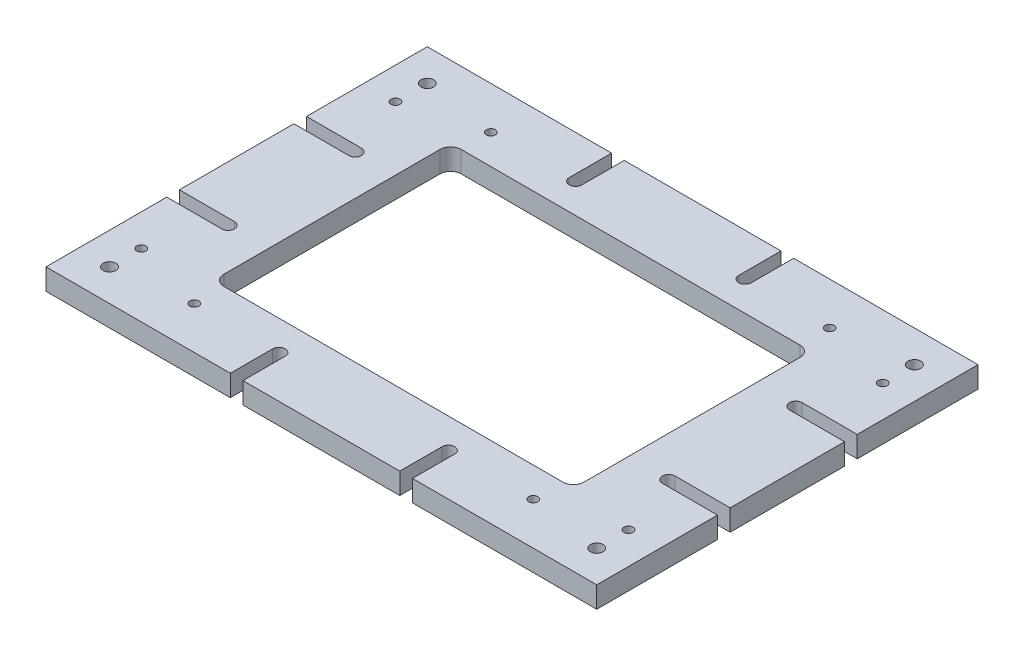
SolidWorks part; units mm, degrees
material "6061 Alloy"
ref_plane "Front Plane" through (0, 0, 0) normal (0, 0, 1) x (1, 0, 0)
ref_plane "Top Plane" through (0, 0, 0) normal (0, 1, 0) x (1, 0, 0)
ref_plane "Right Plane" through (0, 0, 0) normal (1, 0, 0) x (0, 0, -1)
sketch "Sketch1" plane through (0, 0, 0) normal (0, 1, 0) x (1, 0, 0)
  line L1 (-82.55, -57.15) -> (82.55, -57.15)
  line L2 (-82.55, -57.15) -> (-82.55, 57.15)
  line L3 (-82.55, 57.15) -> (82.55, 57.15)
  line L4 (82.55, -57.15) -> (82.55, 57.15)
  line L5 (-82.55, -57.15) -> (82.55, 57.15) construction
  line L6 (-82.55, 57.15) -> (82.55, -57.15) construction
  point P0 (0, 0)
  dimension "D1" = 165.1
  dimension "D2" = 114.3
extrude "Boss-Extrude1" add sketch "Sketch1" along normal blind 6.35
sketch "Sketch2" plane through (0, 6.35, 0) normal (0, 1, 0) x (1, 0, 0)
  line L0 (-49.5, -31.5) -> (-40.5, -31.5) construction
  line L1 (-49.5, -31.5) -> (-49.5, -22.5) construction
  line L2 (-82.55, 57.15) -> (-82.55, -57.15) construction
  line L3 (-82.55, -57.15) -> (82.55, -57.15) construction
  line L4 (-49.5, -31.5) -> (-49.5, 31.5) construction
  line L5 (-49.5, -31.5) -> (49.5, -31.5) construction
  line L6 (82.55, -57.15) -> (82.55, 57.15) construction
  line L9 (82.55, 57.15) -> (-82.55, 57.15) construction
  line L10 (0, 57.15) -> (0, -57.15) construction
  line L11 (-82.55, 0) -> (82.55, 0) construction
  circle A0 centre (-49.5, -31.5) radius 0.635
  circle A1 centre (-40.5, -31.5) radius 0.635
  circle A2 centre (-31.5, -31.5) radius 0.635
  circle A3 centre (-22.5, -31.5) radius 0.635
  circle A4 centre (-13.5, -31.5) radius 0.635
  circle A5 centre (-4.5, -31.5) radius 0.635
  circle A6 centre (4.5, -31.5) radius 0.635
  circle A7 centre (13.5, -31.5) radius 0.635
  circle A8 centre (22.5, -31.5) radius 0.635
  circle A9 centre (31.5, -31.5) radius 0.635
  circle A10 centre (40.5, -31.5) radius 0.635
  circle A11 centre (49.5, -31.5) radius 0.635
  circle A12 centre (-49.5, -22.5) radius 0.635
  circle A13 centre (-40.5, -22.5) radius 0.635
  circle A14 centre (-31.5, -22.5) radius 0.635
  circle A15 centre (-22.5, -22.5) radius 0.635
  circle A16 centre (-13.5, -22.5) radius 0.635
  circle A17 centre (-4.5, -22.5) radius 0.635
  circle A18 centre (4.5, -22.5) radius 0.635
  circle A19 centre (13.5, -22.5) radius 0.635
  circle A20 centre (22.5, -22.5) radius 0.635
  circle A21 centre (31.5, -22.5) radius 0.635
  circle A22 centre (40.5, -22.5) radius 0.635
  circle A23 centre (49.5, -22.5) radius 0.635
  circle A24 centre (-49.5, -13.5) radius 0.635
  circle A25 centre (-40.5, -13.5) radius 0.635
  circle A26 centre (-31.5, -13.5) radius 0.635
  circle A27 centre (-22.5, -13.5) radius 0.635
  circle A28 centre (-13.5, -13.5) radius 0.635
  circle A29 centre (-4.5, -13.5) radius 0.635
  circle A30 centre (4.5, -13.5) radius 0.635
  circle A31 centre (13.5, -13.5) radius 0.635
  circle A32 centre (22.5, -13.5) radius 0.635
  circle A33 centre (31.5, -13.5) radius 0.635
  circle A34 centre (40.5, -13.5) radius 0.635
  circle A35 centre (49.5, -13.5) radius 0.635
  circle A36 centre (-49.5, -4.5) radius 0.635
  circle A37 centre (-40.5, -4.5) radius 0.635
  circle A38 centre (-31.5, -4.5) radius 0.635
  circle A39 centre (-22.5, -4.5) radius 0.635
  circle A40 centre (-13.5, -4.5) radius 0.635
  circle A41 centre (-4.5, -4.5) radius 0.635
  circle A42 centre (4.5, -4.5) radius 0.635
  circle A43 centre (13.5, -4.5) radius 0.635
  circle A44 centre (22.5, -4.5) radius 0.635
  circle A45 centre (31.5, -4.5) radius 0.635
  circle A46 centre (40.5, -4.5) radius 0.635
  circle A47 centre (49.5, -4.5) radius 0.635
  circle A48 centre (-49.5, 4.5) radius 0.635
  circle A49 centre (-40.5, 4.5) radius 0.635
  circle A50 centre (-31.5, 4.5) radius 0.635
  circle A51 centre (-22.5, 4.5) radius 0.635
  circle A52 centre (-13.5, 4.5) radius 0.635
  circle A53 centre (-4.5, 4.5) radius 0.635
  circle A54 centre (4.5, 4.5) radius 0.635
  circle A55 centre (13.5, 4.5) radius 0.635
  circle A56 centre (22.5, 4.5) radius 0.635
  circle A57 centre (31.5, 4.5) radius 0.635
  circle A58 centre (40.5, 4.5) radius 0.635
  circle A59 centre (49.5, 4.5) radius 0.635
  circle A60 centre (-49.5, 13.5) radius 0.635
  circle A61 centre (-40.5, 13.5) radius 0.635
  circle A62 centre (-31.5, 13.5) radius 0.635
  circle A63 centre (-22.5, 13.5) radius 0.635
  circle A64 centre (-13.5, 13.5) radius 0.635
  circle A65 centre (-4.5, 13.5) radius 0.635
  circle A66 centre (4.5, 13.5) radius 0.635
  circle A67 centre (13.5, 13.5) radius 0.635
  circle A68 centre (22.5, 13.5) radius 0.635
  circle A69 centre (31.5, 13.5) radius 0.635
  circle A70 centre (40.5, 13.5) radius 0.635
  circle A71 centre (49.5, 13.5) radius 0.635
  circle A72 centre (-49.5, 22.5) radius 0.635
  circle A73 centre (-40.5, 22.5) radius 0.635
  circle A74 centre (-31.5, 22.5) radius 0.635
  circle A75 centre (-22.5, 22.5) radius 0.635
  circle A76 centre (-13.5, 22.5) radius 0.635
  circle A77 centre (-4.5, 22.5) radius 0.635
  circle A78 centre (4.5, 22.5) radius 0.635
  circle A79 centre (13.5, 22.5) radius 0.635
  circle A80 centre (22.5, 22.5) radius 0.635
  circle A81 centre (31.5, 22.5) radius 0.635
  circle A82 centre (40.5, 22.5) radius 0.635
  circle A83 centre (49.5, 22.5) radius 0.635
  circle A84 centre (-49.5, 31.5) radius 0.635
  circle A85 centre (-40.5, 31.5) radius 0.635
  circle A86 centre (-31.5, 31.5) radius 0.635
  circle A87 centre (-22.5, 31.5) radius 0.635
  circle A88 centre (-13.5, 31.5) radius 0.635
  circle A89 centre (-4.5, 31.5) radius 0.635
  circle A90 centre (4.5, 31.5) radius 0.635
  circle A91 centre (13.5, 31.5) radius 0.635
  circle A92 centre (22.5, 31.5) radius 0.635
  circle A93 centre (31.5, 31.5) radius 0.635
  circle A94 centre (40.5, 31.5) radius 0.635
  circle A95 centre (49.5, 31.5) radius 0.635
  dimension "D1" = 12
  dimension "D7" = 1.27
  dimension "D3" = 9
  dimension "D4" = 9
  dimension "D5" = 49.5
  dimension "D6" = 31.5
  dimension "D2" = 8
hole_wizard "#10-24 Tapped Hole2" positions "Sketch13" profile "Sketch12" tap size "#10-24" standard "Ansi Inch" end condition through all
sketch "Sketch13" plane through (0, 6.35, 0) normal (0, 1, 0) x (-1, 0, 0)
  line L0 (-82.55, -57.15) -> (82.55, -57.15) construction
  line L1 (82.55, -57.15) -> (82.55, 57.15) construction
  line L2 (82.55, 57.15) -> (-82.55, 57.15) construction
  line L3 (82.55, -57.15) -> (82.55, 57.15) construction
  line L4 (-82.55, -57.15) -> (82.55, -57.15) construction
  line L6 (-82.55, 57.15) -> (-82.55, -57.15) construction
  line L7 (-82.55, 57.15) -> (-82.55, -57.15) construction
  line L8 (82.55, 57.15) -> (-82.55, 57.15) construction
  point P0 (73.025, -47.625)
  point P1 (73.025, 47.625)
  point P3 (-73.025, -47.625)
  point P4 (-73.025, 47.625)
  dimension "D1" = 9.525
  dimension "D2" = 9.525
  dimension "D3" = 9.525
  dimension "D4" = 9.525
  dimension "D5" = 9.525
  dimension "D6" = 9.525
  dimension "D7" = 9.525
  dimension "D8" = 9.525
sketch "Sketch12" plane through (-73.025, 6.35, -47.625) normal (1, 0, 0) x (0, 0, 1)
  line L0 (0, 0) -> (0, 6.35)
  line L1 (0, 6.35) -> (1.8986, 6.35)
  line L2 (1.8986, 6.35) -> (1.8986, 0)
  line L5 (1.8986, 0) -> (0, 0)
  line L11 (0, -6.35) -> (0, 107.95) construction
  dimension "Thru Tap Drill Dia." = 3.7973
  dimension "Thru Tap Drill Depth" = 6.35
cosmetic thread "Hole Thread1" parameters "D2"=4.826
cosmetic thread "Hole Thread2" parameters "D2"=4.826
cosmetic thread "Hole Thread3" parameters "D2"=4.826
cosmetic thread "Hole Thread4" parameters "D2"=4.826
hole_wizard "#6-32 Tapped Hole2" positions "Sketch16" profile "Sketch15" tap size "#6-32" standard "Ansi Inch" end condition through all
sketch "Sketch16" plane through (0, 6.35, 0) normal (0, 1, 0) x (-1, 0, 0)
  line L0 (-82.55, -57.15) -> (82.55, -57.15) construction
  line L1 (82.55, -57.15) -> (82.55, 57.15) construction
  line L2 (-82.55, -57.15) -> (82.55, -57.15) construction
  line L3 (-82.55, 57.15) -> (-82.55, -57.15) construction
  line L4 (82.55, 57.15) -> (-82.55, 57.15) construction
  line L5 (82.55, -57.15) -> (82.55, 57.15) construction
  line L6 (-82.55, 57.15) -> (-82.55, -57.15) construction
  line L7 (82.55, 57.15) -> (-82.55, 57.15) construction
  point P0 (50.8, -44.45)
  point P1 (-50.8, -44.45)
  point P3 (-50.8, 44.45)
  point P5 (50.8, 44.45)
  point P21 (-82.55, 0)
  dimension "D1" = 12.7
  dimension "D2" = 31.75
  dimension "D3" = 12.7
  dimension "D4" = 31.75
  dimension "D5" = 12.7
  dimension "D6" = 31.75
  dimension "D7" = 31.75
  dimension "D8" = 12.7
  dimension "D9" = 101.6
  dimension "D10" = 88.9
sketch "Sketch15" plane through (-50.8, 6.35, -44.45) normal (1, 0, 0) x (0, 0, 1)
  line L0 (0, 0) -> (0, 6.35)
  line L1 (0, 6.35) -> (1.3525, 6.35)
  line L2 (1.3525, 6.35) -> (1.3525, 0)
  line L5 (1.3525, 0) -> (0, 0)
  line L11 (0, -6.35) -> (0, 107.95) construction
  dimension "Thru Tap Drill Dia." = 2.7051
  dimension "Thru Tap Drill Depth" = 6.35
cosmetic thread "Hole Thread5" parameters "D2"=3.5052
cosmetic thread "Hole Thread6" parameters "D2"=3.5052
cosmetic thread "Hole Thread7" parameters "D2"=3.5052
cosmetic thread "Hole Thread8" parameters "D2"=3.5052
sketch "Sketch21" plane through (0, 6.35, 0) normal (0, 1, 0) x (1, 0, 0)
  line L0 (-82.55, 19.05) -> (-66.04, 19.05) construction
  line L2 (-82.55, 20.9486) -> (-66.04, 20.9486)
  line L3 (-82.55, 17.1513) -> (-66.04, 17.1513)
  line L4 (-82.55, -19.05) -> (-66.04, -19.05) construction
  line L5 (-82.55, -17.1514) -> (-66.04, -17.1514)
  line L6 (-82.55, -20.9487) -> (-66.04, -20.9487)
  line L7 (-25.4, 57.15) -> (-25.4, 44.45) construction
  line L8 (-23.5013, 57.15) -> (-23.5013, 44.45)
  line L9 (-27.2986, 57.15) -> (-27.2986, 44.45)
  line L10 (25.4, 57.15) -> (25.4, 44.45) construction
  line L11 (27.2987, 57.15) -> (27.2987, 44.45)
  line L12 (23.5014, 57.15) -> (23.5014, 44.45)
  line L13 (66.04, 19.05) -> (82.55, 19.05) construction
  line L14 (66.04, 20.9486) -> (82.55, 20.9486)
  line L15 (66.04, 17.1513) -> (82.55, 17.1513)
  line L16 (66.04, -19.05) -> (82.55, -19.05) construction
  line L17 (66.04, -17.1514) -> (82.55, -17.1514)
  line L18 (66.04, -20.9487) -> (82.55, -20.9487)
  line L19 (-25.4, -57.15) -> (-25.4, -44.45) construction
  line L20 (-82.55, -57.15) -> (82.55, -57.15) construction
  line L21 (-27.2986, -57.15) -> (-27.2986, -44.45)
  line L22 (-23.5013, -57.15) -> (-23.5013, -44.45)
  line L23 (25.4, -57.15) -> (25.4, -44.45) construction
  line L24 (23.5014, -57.15) -> (23.5014, -44.45)
  line L25 (27.2987, -57.15) -> (27.2987, -44.45)
  line L26 (-82.55, 57.15) -> (-82.55, -57.15) construction
  line L27 (82.55, -57.15) -> (82.55, 57.15) construction
  line L28 (82.55, 57.15) -> (-82.55, 57.15) construction
  arc A0 (-82.55, 20.9486) -> (-82.55, 17.1513) centre (-82.55, 19.05) ccw
  arc A1 (-66.04, 17.1513) -> (-66.04, 20.9486) centre (-66.04, 19.05) ccw
  arc A2 (-82.55, -17.1514) -> (-82.55, -20.9487) centre (-82.55, -19.05) ccw
  arc A3 (-66.04, -20.9487) -> (-66.04, -17.1514) centre (-66.04, -19.05) ccw
  arc A4 (-23.5013, 57.15) -> (-27.2986, 57.15) centre (-25.4, 57.15) ccw
  arc A5 (-27.2986, 44.45) -> (-23.5013, 44.45) centre (-25.4, 44.45) ccw
  arc A6 (27.2987, 57.15) -> (23.5014, 57.15) centre (25.4, 57.15) ccw
  arc A7 (23.5014, 44.45) -> (27.2987, 44.45) centre (25.4, 44.45) ccw
  arc A8 (66.04, 20.9486) -> (66.04, 17.1513) centre (66.04, 19.05) ccw
  arc A9 (82.55, 17.1513) -> (82.55, 20.9486) centre (82.55, 19.05) ccw
  arc A10 (66.04, -17.1514) -> (66.04, -20.9487) centre (66.04, -19.05) ccw
  arc A11 (82.55, -20.9487) -> (82.55, -17.1514) centre (82.55, -19.05) ccw
  arc A12 (-27.2986, -57.15) -> (-23.5013, -57.15) centre (-25.4, -57.15) ccw
  arc A13 (-23.5013, -44.45) -> (-27.2986, -44.45) centre (-25.4, -44.45) ccw
  arc A14 (23.5014, -57.15) -> (27.2987, -57.15) centre (25.4, -57.15) ccw
  arc A15 (27.2987, -44.45) -> (23.5014, -44.45) centre (25.4, -44.45) ccw
  point P2 (-74.295, 19.05)
  point P7 (-74.295, -19.05)
  point P16 (-25.4, 50.8)
  point P23 (25.4, 50.8)
  point P30 (74.295, 19.05)
  point P37 (74.295, -19.05)
  point P44 (-25.4, -50.8)
  point P53 (25.4, -50.8)
  dimension "D3" = 3.7973
  dimension "D4" = 3.7973
  dimension "D5" = 3.7973
  dimension "D6" = 3.7973
  dimension "D7" = 3.7973
  dimension "D8" = 3.7973
  dimension "D9" = 16.51
  dimension "D10" = 16.51
  dimension "D11" = 12.7
  dimension "D12" = 12.7
  dimension "D13" = 16.51
  dimension "D14" = 16.51
  dimension "D15" = 12.7
  dimension "D16" = 12.7
  dimension "D17" = 0
  dimension "D18" = 0
  dimension "D19" = 0
  dimension "D20" = 0
  dimension "D21" = 0
  dimension "D22" = 0
  dimension "D23" = 50.8
  dimension "D24" = 38.1
  dimension "D25" = 38.1
  dimension "D26" = 38.1
  dimension "D27" = 57.15
  dimension "D28" = 3.7973
  dimension "D29" = 3.7973
extrude "Cut-Extrude10" cut sketch "Sketch21" against normal through all
hole_wizard "#6-32 Tapped Hole1" positions "Sketch23" profile "Sketch22" tap size "#6-32" standard "Ansi Inch" end condition through all
sketch "Sketch23" plane through (0, 6.35, 0) normal (0, 1, 0) x (-1, 0, 0)
  line L0 (82.55, -57.15) -> (82.55, -20.9486) construction
  line L1 (-82.55, 57.15) -> (-82.55, 20.9486) construction
  line L2 (82.55, 57.15) -> (27.2986, 57.15) construction
  line L3 (-27.2987, 57.15) -> (-82.55, 57.15) construction
  line L4 (-82.55, -57.15) -> (-27.2987, -57.15) construction
  line L5 (27.2986, -57.15) -> (82.55, -57.15) construction
  point P0 (73.025, -38.1)
  point P1 (73.025, 38.1)
  point P3 (-73.025, -38.1)
  point P5 (-73.025, 38.1)
  dimension "D1" = 9.525
  dimension "D2" = 9.525
  dimension "D3" = 9.525
  dimension "D4" = 9.525
  dimension "D5" = 19.05
  dimension "D6" = 19.05
  dimension "D7" = 19.05
  dimension "D8" = 19.05
cosmetic thread "Hole Thread9" parameters "D2"=3.5052
cosmetic thread "Hole Thread10" parameters "D2"=3.5052
cosmetic thread "Hole Thread11" parameters "D2"=3.5052
cosmetic thread "Hole Thread12" parameters "D2"=3.5052
sketch "Sketch22" plane through (-73.025, 6.35, -38.1) normal (1, 0, 0) x (0, 0, 1)
  line L0 (0, 0) -> (0, 6.35)
  line L1 (0, 6.35) -> (1.3525, 6.35)
  line L2 (1.3525, 6.35) -> (1.3525, 0)
  line L5 (1.3525, 0) -> (0, 0)
  line L11 (0, -6.35) -> (0, 107.95) construction
  dimension "Thru Tap Drill Dia." = 2.7051
  dimension "Thru Tap Drill Depth" = 6.35
sketch "Sketch24" plane through (0, 6.35, 0) normal (0, 1, 0) x (1, 0, 0)
  line L1 (53.975, -35.56) -> (-53.975, -35.56)
  line L2 (53.975, -35.56) -> (53.975, 35.56)
  line L3 (53.975, 35.56) -> (-53.975, 35.56)
  line L4 (-53.975, -35.56) -> (-53.975, 35.56)
  line L5 (53.975, -35.56) -> (-53.975, 35.56) construction
  line L6 (53.975, 35.56) -> (-53.975, -35.56) construction
  point P0 (0, 0)
  dimension "D1" = 71.12
  dimension "D2" = 107.95
extrude "Cut-Extrude11" cut sketch "Sketch24" against normal through all
fillet "Fillet1" radius 3.175 4 edges at (53.975, 3.175, 35.56) (-53.975, 3.175, 35.56) (53.975, 3.175, -35.56) (-53.975, 3.175, -35.56)
sketch "Sketch25" plane through (0, 6.35, 0) normal (0, 1, 0) x (1, 0, 0)
  line L1 (-49.5, 31.5) -> (-50.8, 31.5)
  line L2 (-49.5, 31.5) -> (-49.5, 44.45)
  line L3 (-49.5, 44.45) -> (-50.8, 44.45)
  line L4 (-50.8, 31.5) -> (-50.8, 44.45)
  line L5 (49.5, 31.5) -> (50.8, 31.5)
  line L6 (49.5, 31.5) -> (49.5, 44.45)
  line L7 (49.5, 44.45) -> (50.8, 44.45)
  line L8 (50.8, 31.5) -> (50.8, 44.45)
  line L9 (-50.8, -44.45) -> (-49.5, -44.45)
  line L10 (-50.8, -44.45) -> (-50.8, -31.5)
  line L11 (-50.8, -31.5) -> (-49.5, -31.5)
  line L12 (-49.5, -44.45) -> (-49.5, -31.5)
  line L13 (50.8, -44.45) -> (49.5, -44.45)
  line L14 (50.8, -44.45) -> (50.8, -31.5)
  line L15 (50.8, -31.5) -> (49.5, -31.5)
  line L16 (49.5, -44.45) -> (49.5, -31.5)
  dimension "D1" = 12.95
  dimension "D2" = 1.3
  dimension "D3" = 12.95
  dimension "D4" = 1.3
  dimension "D5" = 12.95
  dimension "D6" = 1.3
sketch "Sketch26" plane through (0, 6.35, 0) normal (0, 1, 0) x (1, 0, 0)
  line L1 (-50.8, 44.45) -> (50.8, 44.45)
  line L2 (-50.8, 44.45) -> (-50.8, -44.45)
  line L3 (-50.8, -44.45) -> (50.8, -44.45)
  line L4 (50.8, 44.45) -> (50.8, -44.45)
  dimension "D1" = 101.6
  dimension "D2" = 88.9
sketch "Sketch27" plane through (0, 6.35, 0) normal (0, 1, 0) x (1, 0, 0)
  line L0 (23.5014, 57.15) -> (-23.5013, 57.15) construction
  line L1 (-63.5, 57.15) -> (63.5, 57.15)
  line L2 (-63.5, 57.15) -> (-63.5, -57.15)
  line L3 (-63.5, -57.15) -> (63.5, -57.15)
  line L4 (63.5, 57.15) -> (63.5, -57.15)
  line L5 (-82.55, 17.1513) -> (-82.55, -17.1514) construction
  line L7 (-31.75, 57.15) -> (-19.05, 57.15)
  line L8 (-31.75, 57.15) -> (-31.75, 40.64)
  line L9 (-31.75, 40.64) -> (-19.05, 40.64)
  line L10 (-19.05, 57.15) -> (-19.05, 40.64)
  line L11 (19.05, 57.15) -> (31.75, 57.15)
  line L12 (19.05, 57.15) -> (19.05, 40.64)
  line L13 (19.05, 40.64) -> (31.75, 40.64)
  line L14 (31.75, 57.15) -> (31.75, 40.64)
  circle A0 centre (-50.8, -44.45) radius 1.3526 construction
  dimension "D8" = 12.7
  dimension "D9" = 12.7
  dimension "D1" = 114.3
  dimension "D2" = 127
  dimension "D3" = 19.05
  dimension "D4" = 31.75
  dimension "D5" = 31.75
  dimension "D6" = 12.7
  dimension "D7" = 12.7
  dimension "D14" = 16.51
  dimension "D15" = 16.51
equation "\"D4@Sketch16\" = \"D2@Sketch16\""
equation "\"D3@Sketch16\"=\"D1@Sketch16\""
equation "\"D6@Sketch16\"=\"D2@Sketch16\""
equation "\"D5@Sketch16\"=\"D1@Sketch16\""
equation "\"D7@Sketch16\"=\"D2@Sketch16\""
equation "\"D8@Sketch16\"=\"D1@Sketch16\""
equation "\"D3@Sketch13\" = \"D1@Sketch13\""
equation "\"D4@Sketch13\"=\"D2@Sketch13\""
equation "\"D6@Sketch13\"=\"D2@Sketch13\""
equation "\"D5@Sketch13\"=\"D1@Sketch13\""
equation "\"D8@Sketch13\"=\"D1@Sketch13\""
equation "\"D7@Sketch13\" = \"D2@Sketch13\""
equation "\"D8@Sketch21\" = \"D7@Sketch21\""
equation "\"D10@Sketch21\" = \"D9@Sketch21\""
equation "\"D13@Sketch21\" = \"D9@Sketch21\""
equation "\"D14@Sketch21\" = \"D9@Sketch21\""
equation "\"D12@Sketch21\" = \"D11@Sketch21\""
equation "\"D25@Sketch21\" = \"D24@Sketch21\""
